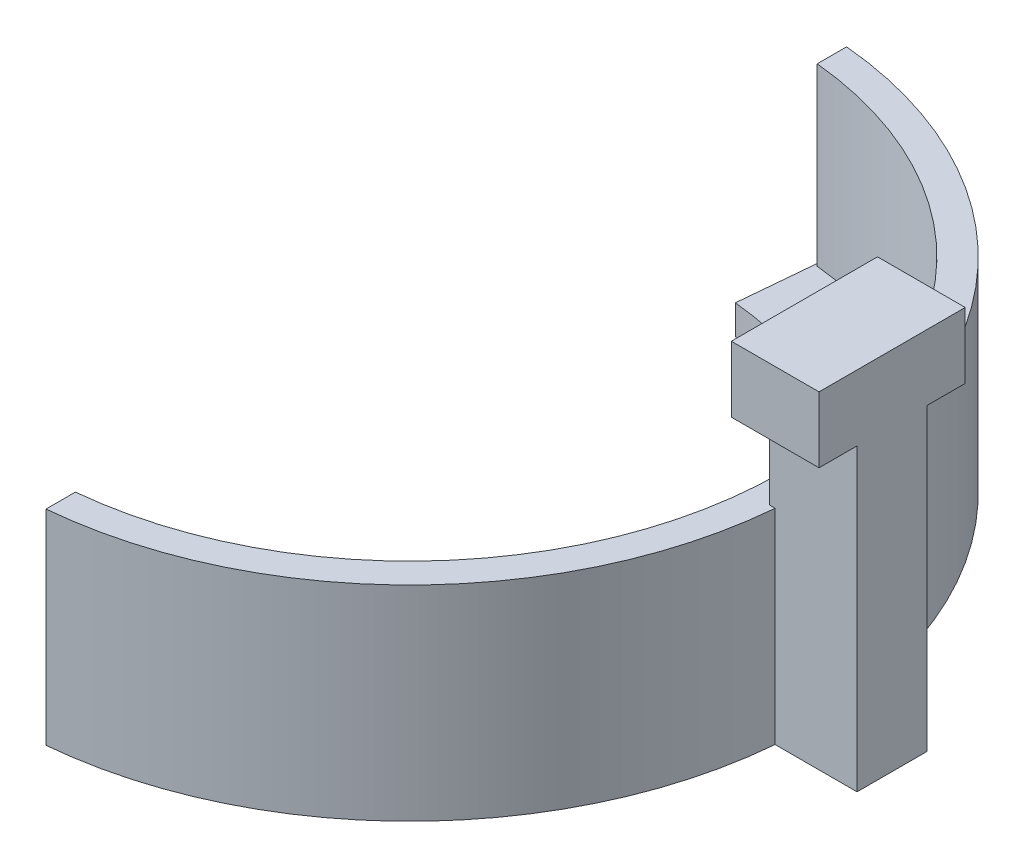
SolidWorks part; units mm, degrees
ref_plane "Front Plane" through (0, 0, 0) normal (0, 0, 1) x (1, 0, 0)
ref_plane "Top Plane" through (0, 0, 0) normal (0, 1, 0) x (1, 0, 0)
ref_plane "Right Plane" through (0, 0, 0) normal (1, 0, 0) x (0, 0, -1)
sketch "Sketch1" plane through (0, 0, 0) normal (0, 1, 0) x (1, 0, 0)
  line L4 (2.5, 27.3861) -> (2.5, 25.3772)
  line L6 (-2.5, 0) -> (2.5, 0) construction
  line L7 (2.5, -25.3772) -> (2.5, -27.3861)
  arc A2 (2.5, -27.3861) -> (2.5, 27.3861) centre (0, 0) ccw
  arc A5 (2.5, -25.3772) -> (2.5, 25.3772) centre (0, 0) ccw
  point P4 (24.3858, 7.4555)
  point P12 (26.2984, 8.0402)
extrude "Boss-Extrude1" add sketch "Sketch1" along normal blind 12
sketch "Sketch2" plane through (0, 0, 0) normal (0, 1, 0) x (1, 0, 0)
  line L0 (2.5, 27.3861) -> (1.8636, 20.4151)
  line L1 (2.5, -27.3861) -> (1.8636, -20.4151)
  arc A0 (2.5, 27.3861) -> (2.5, -27.3861) centre (0, 0) cw
  arc A1 (1.8636, 20.4151) -> (1.8636, -20.4151) centre (0, 0) cw
  dimension "D1" = 7
extrude "Boss-Extrude2" add sketch "Sketch2" against normal blind 2
sketch "Sketch4" plane through (0, -2, 0) normal (0, 1, 0) x (1, 0, 0)
  line L1 (27, 2.4) -> (33, 2.4)
  line L2 (27, 2.4) -> (27, -2.4)
  line L3 (27, -2.4) -> (33, -2.4)
  line L4 (33, 2.4) -> (33, -2.4)
  line L5 (30, -2.4) -> (30, 2.4) construction
  line L6 (27, 0) -> (33, 0) construction
  point P0 (30, 0)
  dimension "D1" = 6
  dimension "D2" = 4.8
  dimension "D3" = 30
extrude "Boss-Extrude3" add sketch "Sketch4" along normal blind 22
sketch "Sketch5" plane through (0, 20, 0) normal (0, 1, 0) x (1, 0, 0)
  line L0 (33, -2.4) -> (33, 2.4) construction
  line L1 (27, 5) -> (33, 5)
  line L2 (27, 5) -> (27, -5)
  line L3 (27, -5) -> (33, -5)
  line L4 (33, 5) -> (33, -5)
  line L5 (30, -5) -> (30, 5) construction
  line L6 (27, 0) -> (33, 0) construction
  point P0 (30, 0)
  dimension "D1" = 3
  dimension "D2" = 6
  dimension "D3" = 10
extrude "Boss-Extrude4" add sketch "Sketch5" along normal blind 3 and the other way blind 1.5
ref_plane "Plane1" through (0, 18.5, 0) normal (0, -1, 0) x (-1, 0, 0)
